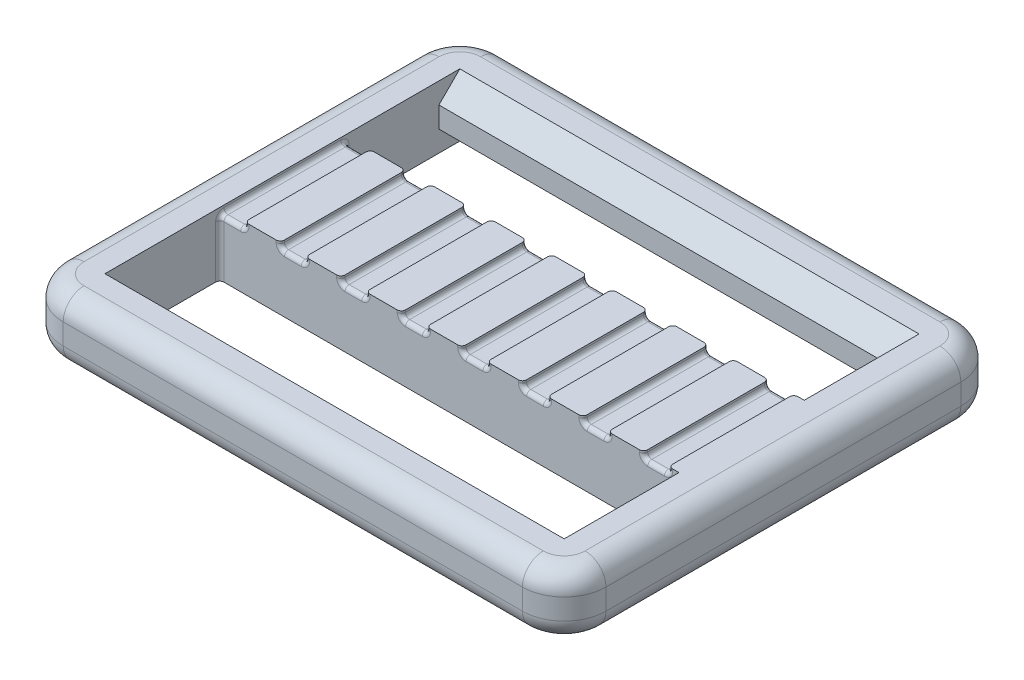
SolidWorks part; units mm, degrees
ref_plane "前视基准面" through (0, 0, 0) normal (0, 0, 1) x (1, 0, 0)
ref_plane "上视基准面" through (0, 0, 0) normal (0, 1, 0) x (1, 0, 0)
ref_plane "右视基准面" through (0, 0, 0) normal (1, 0, 0) x (0, 0, -1)
sketch "草图1" plane through (0, 0, 0) normal (0, 1, 0) x (1, 0, 0)
  line L0 (0, 0) -> (13, 0) construction
  line L1 (-11, 10.5) -> (11, 10.5)
  line L2 (-13, 8.5) -> (-13, -8.5)
  line L3 (-11, -10.5) -> (11, -10.5)
  line L4 (13, 8.5) -> (13, -8.5)
  line L5 (-13, 10.5) -> (13, -10.5) construction
  line L6 (-13, -10.5) -> (13, 10.5) construction
  line L7 (0, 10.5) -> (0, 0) construction
  line L8 (11, -7.5) -> (11, -3)
  line L9 (-11, 7.5) -> (11, 7.5)
  line L10 (-11, 7.5) -> (-11, 3)
  line L11 (-11, 3) -> (11, 3)
  line L12 (11, 7.5) -> (11, 3)
  line L13 (-11, 7.5) -> (11, 3) construction
  line L14 (-11, 3) -> (11, 7.5) construction
  line L15 (-11, -3) -> (11, -3)
  line L16 (-11, -7.5) -> (-11, -3)
  line L17 (-11, -7.5) -> (11, -7.5)
  arc A0 (11, -10.5) -> (13, -8.5) centre (11, -8.5) ccw
  arc A1 (-13, -8.5) -> (-11, -10.5) centre (-11, -8.5) ccw
  arc A2 (11, 10.5) -> (13, 8.5) centre (11, 8.5) cw
  arc A3 (-11, 10.5) -> (-13, 8.5) centre (-11, 8.5) ccw
  point P0 (0, 0)
  point P9 (0, 5.25)
  dimension "D5" = 2
  dimension "D1" = 6
  dimension "D2" = 26
  dimension "D3" = 22
  dimension "D4" = 4.5
extrude "凸台-拉伸1" add sketch "草图1" along normal blind 3
sketch "草图3" plane through (0, 3, 0) normal (0, 1, 0) x (1, 0, 0)
  line L0 (-11, 3) -> (-11, -3) construction
  line L1 (11, -3) -> (-11, -3) construction
  line L2 (-11, 3) -> (-9.8, 3)
  line L3 (-11, 3) -> (-11, -3)
  line L4 (-11, -3) -> (-9.8, -3)
  line L5 (-9.8, 3) -> (-9.8, -3)
  line L6 (-8.1, 3) -> (-6.9, 3)
  line L7 (-8.1, 3) -> (-8.1, -3)
  line L8 (-8.1, -3) -> (-6.9, -3)
  line L9 (-6.9, 3) -> (-6.9, -3)
  line L10 (-8.1, 3) -> (-8.1, -3) construction
  line L11 (-5.2, 3) -> (-4, 3)
  line L12 (-5.2, 3) -> (-5.2, -3)
  line L13 (-5.2, -3) -> (-4, -3)
  line L14 (-4, 3) -> (-4, -3)
  line L15 (-5.2, 3) -> (-5.2, -3) construction
  line L16 (-2.3, 3) -> (-1.1, 3)
  line L17 (-2.3, 3) -> (-2.3, -3)
  line L18 (-2.3, -3) -> (-1.1, -3)
  line L19 (-1.1, 3) -> (-1.1, -3)
  line L20 (-2.3, 3) -> (-2.3, -3) construction
  line L21 (0.6, 3) -> (1.8, 3)
  line L22 (0.6, 3) -> (0.6, -3)
  line L23 (0.6, -3) -> (1.8, -3)
  line L24 (1.8, 3) -> (1.8, -3)
  line L25 (0.6, 3) -> (0.6, -3) construction
  line L26 (3.5, 3) -> (4.7, 3)
  line L27 (3.5, 3) -> (3.5, -3)
  line L28 (3.5, -3) -> (4.7, -3)
  line L29 (4.7, 3) -> (4.7, -3)
  line L30 (3.5, 3) -> (3.5, -3) construction
  line L31 (6.4, 3) -> (7.6, 3)
  line L32 (6.4, 3) -> (6.4, -3)
  line L33 (6.4, -3) -> (7.6, -3)
  line L34 (7.6, 3) -> (7.6, -3)
  line L35 (6.4, 3) -> (6.4, -3) construction
  line L36 (9.3, 3) -> (10.5, 3)
  line L37 (9.3, 3) -> (9.3, -3)
  line L38 (9.3, -3) -> (10.5, -3)
  line L39 (10.5, 3) -> (10.5, -3)
  line L40 (9.3, 3) -> (9.3, -3) construction
  dimension "D1" = 1.2
  dimension "D2" = 8
extrude "切除-拉伸1" cut sketch "草图3" against normal blind 0.3
fillet "圆角1" radius 0.2 64 edges at (10.5, 2.85, -3) (9.3, 2.85, -3) (10.5, 2.85, 3) (9.3, 2.85, 3) (7.6, 2.85, -3) (6.4, 2.85, -3) (7.6, 2.85, 3) (6.4, 2.85, 3) (4.7, 2.85, -3) (3.5, 2.85, -3) (4.7, 2.85, 3) (3.5, 2.85, 3) (1.8, 2.85, -3) (0.6, 2.85, -3) (1.8, 2.85, 3) (0.6, 2.85, 3) (-1.1, 2.85, -3) (-2.3, 2.85, -3) (-1.1, 2.85, 3) (-2.3, 2.85, 3) (-4, 2.85, -3) (-5.2, 2.85, -3) (-4, 2.85, 3) (-5.2, 2.85, 3) (-6.9, 2.85, -3) (-8.1, 2.85, -3) (-6.9, 2.85, 3) (-8.1, 2.85, 3) (-9.8, 2.85, -3) (-11, 1.35, -3) (-9.8, 2.85, 3) (-11, 1.35, 3) (9.9, 2.7, -3) (10.5, 2.7, 0) (9.9, 2.7, 3) (9.3, 2.7, 0) (7, 2.7, -3) (7.6, 2.7, 0) (7, 2.7, 3) (6.4, 2.7, 0) (4.1, 2.7, -3) (4.7, 2.7, 0) (4.1, 2.7, 3) (3.5, 2.7, 0) (1.2, 2.7, -3) (1.8, 2.7, 0) (1.2, 2.7, 3) (0.6, 2.7, 0) (-1.7, 2.7, -3) (-1.1, 2.7, 0) (-1.7, 2.7, 3) (-2.3, 2.7, 0) (-4.6, 2.7, -3) (-4, 2.7, 0) (-4.6, 2.7, 3) (-5.2, 2.7, 0) (-7.5, 2.7, -3) (-6.9, 2.7, 0) (-7.5, 2.7, 3) (-8.1, 2.7, 0) (-10.4, 2.7, -3) (-9.8, 2.7, 0) (-10.4, 2.7, 3) (-11, 2.7, 0)
chamfer "倒角1" distance 1 angle 45 4 edges at (0, 3, 7.5) (0, 3, -7.5) (0, 0, 7.5) (0, 0, -7.5)
fillet "圆角2" radius 1 16 edges at (12.4142, 3, -9.9142) (13, 3, 0) (12.4142, 3, 9.9142) (0, 3, 10.5) (-12.4142, 3, 9.9142) (-13, 3, 0) (-12.4142, 3, -9.9142) (12.4142, 0, -9.9142) (13, 0, 0) (12.4142, 0, 9.9142) (0, 0, 10.5) (-12.4142, 0, 9.9142) (-13, 0, 0) (-12.4142, 0, -9.9142) (0, 3, -10.5) (0, 0, -10.5)
